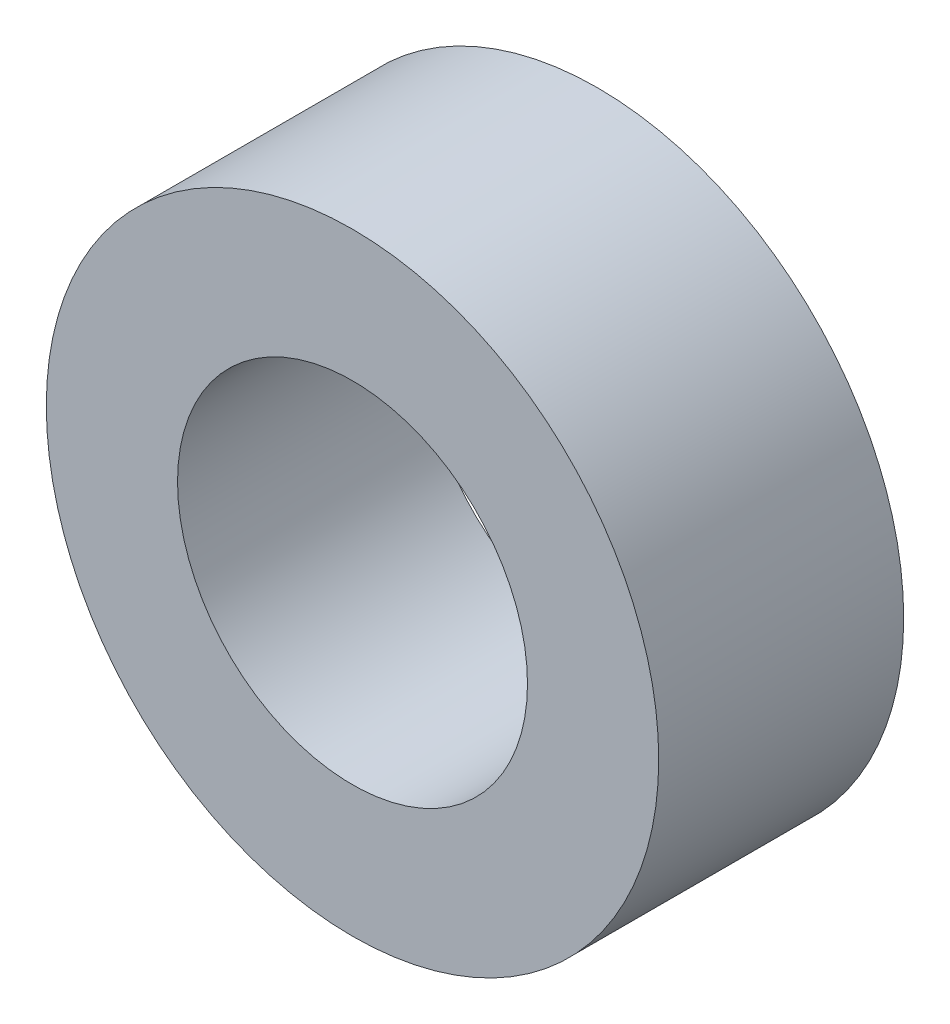
SolidWorks part; units mm, degrees
ref_plane "Front Plane" through (0, 0, 0) normal (0, 0, 1) x (1, 0, 0)
ref_plane "Top Plane" through (0, 0, 0) normal (0, 1, 0) x (1, 0, 0)
ref_plane "Right Plane" through (0, 0, 0) normal (1, 0, 0) x (0, 0, -1)
sketch "Sketch1" plane through (0, 0, 0) normal (0, 0, 1) x (1, 0, 0)
  line L0 (0, -5.5263) -> (0, -106.7984) construction
  line L5 (-87.2458, -40.0667) -> (88.0526, -40.0667) construction
  circle A4 centre (0.4034, -40.0667) radius 17.5
  circle A5 centre (0.4034, -40.0667) radius 10
  dimension "D9" = 20
  dimension "D10" = 35
extrude "Boss-Extrude1" add sketch "Sketch1" along normal blind 14
